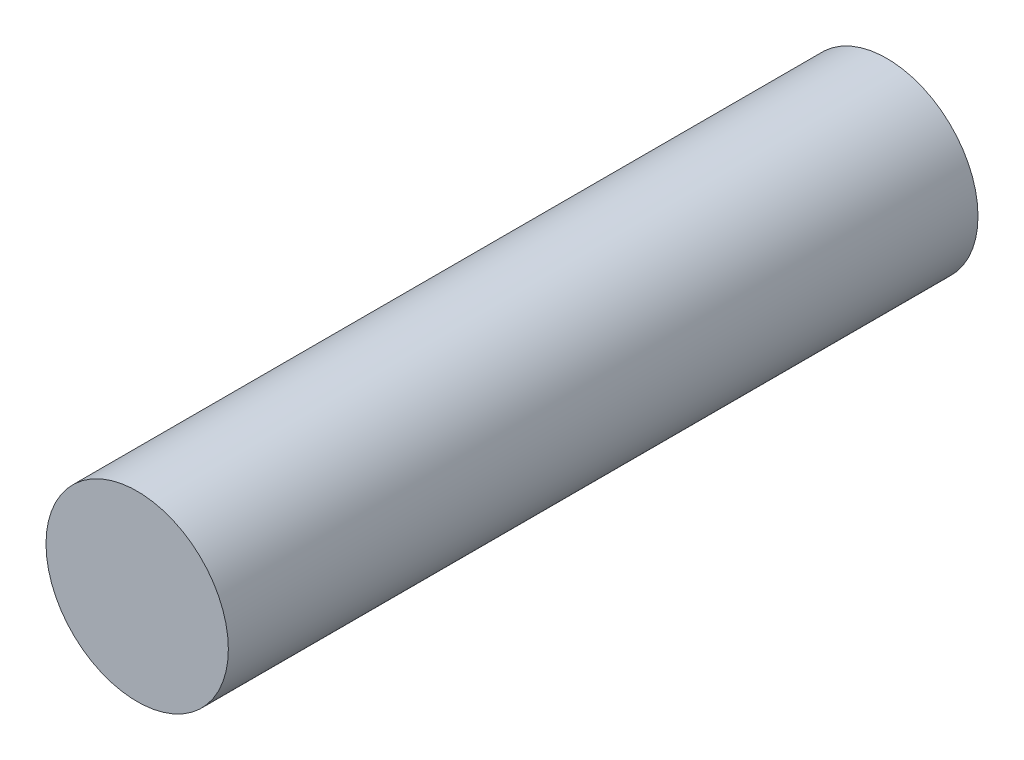
SolidWorks part; units mm, degrees
ref_plane "Front Plane" through (0, 0, 0) normal (0, 0, 1) x (1, 0, 0)
ref_plane "Top Plane" through (0, 0, 0) normal (0, 1, 0) x (1, 0, 0)
ref_plane "Right Plane" through (0, 0, 0) normal (1, 0, 0) x (0, 0, -1)
sketch "Sketch1" plane through (0, 0, 0) normal (0, 0, 1) x (1, 0, 0)
  circle A0 centre (0, 0) radius 2.25
  dimension "D1" = 4.5
extrude "Boss-Extrude1" add sketch "Sketch1" along normal blind 18.5
sketch "Sketch2" plane through (0, 0, 0) normal (0, 0, 1) x (1, 0, 0)
  circle A0 centre (0, 0) radius 3 construction
